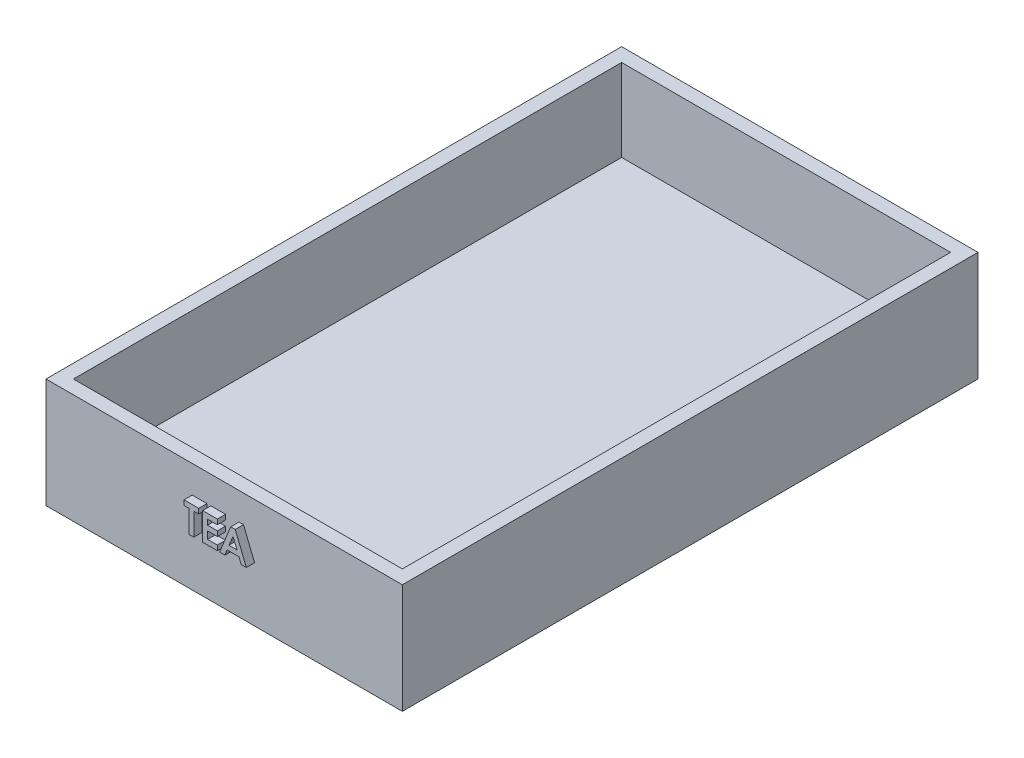
SolidWorks part; units mm, degrees
ref_plane "Front Plane" through (0, 0, 0) normal (0, 0, 1) x (1, 0, 0)
ref_plane "Top Plane" through (0, 0, 0) normal (0, 1, 0) x (1, 0, 0)
ref_plane "Right Plane" through (0, 0, 0) normal (1, 0, 0) x (0, 0, -1)
sketch "Sketch1" plane through (0, 0, 0) normal (0, 1, 0) x (1, 0, 0)
  line L1 (0, 0) -> (130, 0)
  line L2 (0, 0) -> (0, 210)
  line L3 (0, 210) -> (130, 210)
  line L4 (130, 0) -> (130, 210)
  dimension "D1" = 210
  dimension "D2" = 130
extrude "Boss-Extrude1" add sketch "Sketch1" along normal blind 10
sketch "Sketch2" plane through (0, 10, 0) normal (0, 1, 0) x (1, 0, 0)
  line L14 (5, 5) -> (125, 5)
  line L15 (125, 5) -> (125, 205)
  line L16 (5, 205) -> (5, 5)
  line L17 (125, 205) -> (5, 205)
  line L18 (5, 5) -> (125, 5)
  line L19 (125, 5) -> (125, 205)
  line L20 (5, 205) -> (5, 5)
  line L21 (125, 205) -> (5, 205)
  line L32 (0, 0) -> (130, 0)
  line L33 (130, 0) -> (130, 210)
  line L34 (130, 210) -> (0, 210)
  line L35 (0, 210) -> (0, 0)
  line L36 (0, 0) -> (130, 0)
  line L37 (130, 0) -> (130, 210)
  line L38 (130, 210) -> (0, 210)
  line L39 (0, 210) -> (0, 0)
  dimension "D1" = 5
  dimension "D2" = 0
extrude "Boss-Extrude2" add sketch "Sketch2" along normal blind 30
sketch "Sketch3" plane through (0, 0, 0) normal (0, 0, 1) x (1, 0, 0)
  line L0 (0, 20) -> (130, 20) construction
  line L1 (0, 40) -> (0, 0) construction
  line L2 (130, 40) -> (130, 0) construction
  text T0 "<b>TEA</b>" font "Century Gothic" height 10
extrude "Boss-Extrude3" add sketch "Sketch3" along normal blind 3
